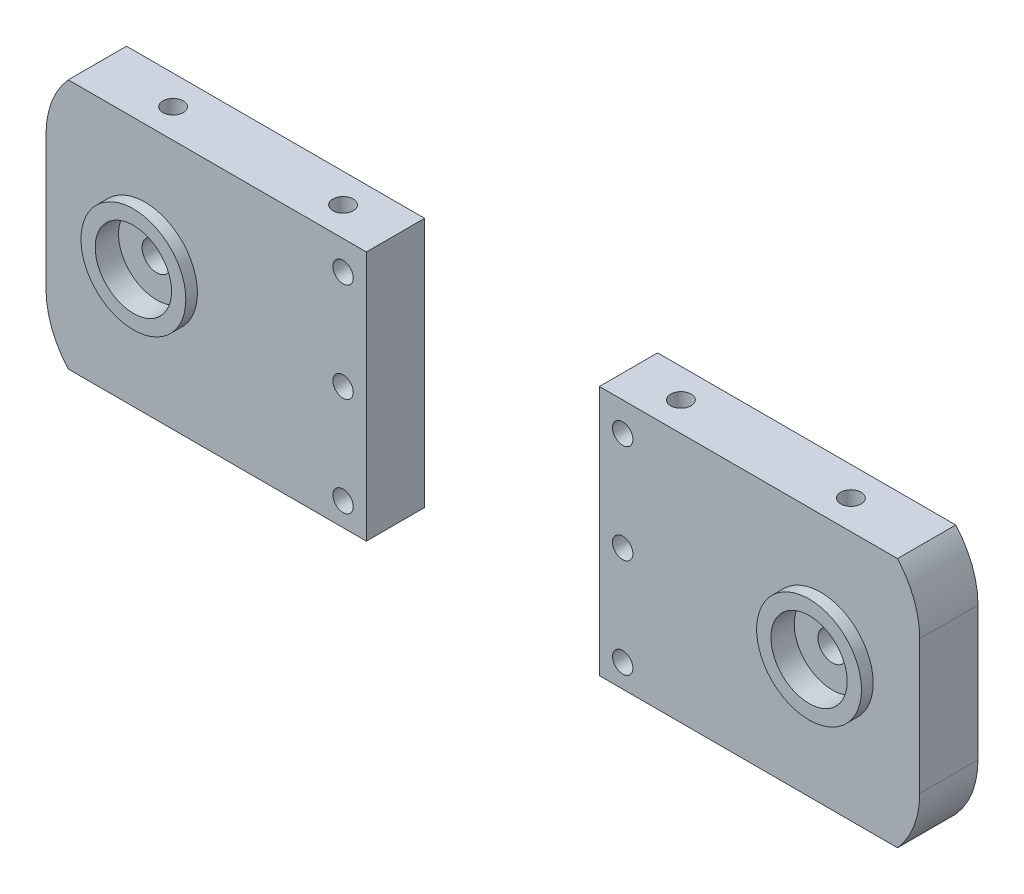
SolidWorks part; units mm, degrees
ref_plane "Ön Düzlem" through (0, 0, 0) normal (0, 0, 1) x (1, 0, 0)
ref_plane "Üst Düzlem" through (0, 0, 0) normal (0, 1, 0) x (1, 0, 0)
ref_plane "Sağ Düzlem" through (0, 0, 0) normal (1, 0, 0) x (0, 0, -1)
sketch "Çizim1" plane through (0, 0, 0) normal (0, 0, 1) x (1, 0, 0)
  line L1 (15, 0) -> (135, 0)
  line L2 (0, 15) -> (0, 38)
  line L3 (15, 53) -> (135, 53)
  line L4 (150, 15) -> (150, 38)
  line L5 (45, 53) -> (105, 53)
  line L6 (45, 53) -> (45, 0)
  line L7 (45, 0) -> (105, 0)
  line L8 (105, 53) -> (105, 0)
  line L9 (45, 53) -> (55, 53)
  line L10 (45, 53) -> (45, 0)
  line L11 (45, 0) -> (55, 0)
  line L12 (55, 53) -> (55, 0)
  line L13 (105, 53) -> (95, 53)
  line L14 (105, 53) -> (105, 1.2346)
  line L15 (105, 1.2346) -> (95, 1.2346)
  line L16 (95, 53) -> (95, 1.2346)
  line L17 (55, 48) -> (95, 48)
  line L18 (55, 48) -> (55, 5)
  line L19 (55, 5) -> (95, 5)
  line L20 (95, 48) -> (95, 5)
  arc A0 (150, 15) -> (135, 0) centre (135, 15) cw
  arc A1 (150, 38) -> (135, 53) centre (135, 38) ccw
  arc A2 (15, 0) -> (0, 15) centre (15, 15) cw
  arc A3 (15, 53) -> (0, 38) centre (15, 38) ccw
  circle A4 centre (17, 27.41) radius 12.5
  circle A5 centre (133, 27.41) radius 12.5
  circle A6 centre (51, 43) radius 1.75
  circle A7 centre (51, 26) radius 1.75
  circle A8 centre (51, 9) radius 1.75
  circle A9 centre (99, 26) radius 1.75
  circle A10 centre (99, 9) radius 1.75
  circle A11 centre (99, 43) radius 1.75
  point P11 (0, 0)
  dimension "D1" = 15
  dimension "D2" = 17
  dimension "D4" = 27.41
  dimension "D5" = 27.41
  dimension "D8" = 4
  dimension "D9" = 10
  dimension "D3" = 17
  dimension "D6" = 60
  dimension "D7" = 45
  dimension "D12" = 5
  dimension "D13" = 5
  dimension "D10" = 3
  dimension "D11" = 2
extrude "Yükseklik-Ekstrüzyon1" add sketch "Çizim1" along normal blind 10 contours L3 A3 L2 A2 L1 L6 A4 | L12 L3 L6 L1 A8 A7 A6 | L3 L16 L1 L8 A11 A10 A9 | L4 A1 L3 L8 L1 A0 A5 | L12 L17 L16 L5 | L19 L12 L7 L8 L15 L16
sketch "Çizim7" plane through (0, 0, 0) normal (0, 0, -1) x (-1, 0, 0)
  circle A0 centre (-133, 27.41) radius 12.5
  circle A1 centre (-133, 27.41) radius 2.5
extrude "Yükseklik-Ekstrüzyon8" add sketch "Çizim7" against normal blind 4 from offset 4 offset against normal yes
sketch "Çizim8" plane through (0, 0, 8) normal (0, 0, 1) x (1, 0, 0)
  circle A0 centre (133, 27.41) radius 2.5
  circle A1 centre (133, 27.41) radius 6.55
  circle A2 centre (133, 27.41) radius 9
extrude "Yükseklik-Ekstrüzyon9" add sketch "Çizim8" along normal blind 4 contours A2 A1
pattern_linear "LÇoğaltma1" count 2 spacing 116 along (-1, 0, 0) of "Yükseklik-Ekstrüzyon9", "Yükseklik-Ekstrüzyon8"
sketch "Çizim11" plane through (0, 0, 10) normal (0, 0, 1) x (1, 0, 0)
  line L0 (55, 48) -> (95, 48) construction
  line L1 (0, 5) -> (150, 5)
  line L2 (0, 5) -> (0, 48)
  line L3 (0, 48) -> (150, 48)
  line L4 (150, 5) -> (150, 48)
  line L5 (55, 5) -> (95, 5) construction
  line L7 (0, 48) -> (156.0546, 48)
  line L8 (0, 48) -> (0, 62.6003)
  line L9 (0, 62.6003) -> (156.0546, 62.6003)
  line L10 (156.0546, 48) -> (156.0546, 62.6003)
  line L11 (0, 5) -> (161.9978, 5)
  line L12 (0, 5) -> (0, -18.6878)
  line L13 (0, -18.6878) -> (161.9978, -18.6878)
  line L14 (161.9978, 5) -> (161.9978, -18.6878)
  line M2 (15, 0) -> (135, 0)
  arc M3 (135, 0) -> (150, 15) centre (135, 15) ccw
  arc M5 (150, 38) -> (135, 53) centre (135, 38) ccw
  line M6 (135, 53) -> (15, 53)
  arc M7 (15, 53) -> (0, 38) centre (15, 38) ccw
  arc M9 (0, 15) -> (15, 0) centre (15, 15) ccw
  line M11 (55, 48) -> (95, 48)
  line M15 (95, 5) -> (55, 5)
extrude "Kes-Ekstrüzyon3" cut sketch "Çizim11" against normal blind 10 contours L7 L10 L9 L8 L3 M7 M6 M5 | L3 M7 M11 M5 M6 | L1 M9 M2 M3 M15 | L14 L11 L1 L12 L13 M3 M2 M9
sketch "Çizim13" plane through (0, 0, 8) normal (0, 0, 1) x (1, 0, 0)
  circle A0 centre (133, 27.41) radius 12.5
  circle A1 centre (133, 27.41) radius 9
  circle A2 centre (17, 27.41) radius 12.5
  circle A3 centre (17, 27.41) radius 9
extrude "Yükseklik-Ekstrüzyon10" add sketch "Çizim13" along normal blind 2
sketch "Çizim12" plane through (0, 48, 0) normal (0, 1, 0) x (1, 0, 0)
  line L0 (55, -10) -> (55, 0) construction
  line L1 (3.8197, -10) -> (3.8197, 0) construction
  line L2 (95, -10) -> (95, 0) construction
  line L3 (146.1803, 0) -> (146.1803, -10) construction
  circle A0 centre (46, -5) radius 1.75
  circle A1 centre (16.8197, -5) radius 1.75
  circle A2 centre (104, -5) radius 1.75
  circle A3 centre (133.1803, -5) radius 1.75
  dimension "D1" = 9
  dimension "D3" = 9
  dimension "D2" = 13
  dimension "D4" = 13
extrude "Kes-Ekstrüzyon4" cut sketch "Çizim12" against normal blind 10
sketch "Çizim14" plane through (0, 5, 0) normal (0, -1, 0) x (1, 0, 0)
  line L0 (146.1803, 10) -> (146.1803, 0) construction
  line L1 (95, 10) -> (95, 0) construction
  line L2 (55, 10) -> (55, 0) construction
  line L3 (3.8197, 0) -> (3.8197, 10) construction
  circle A0 centre (16.8197, 5) radius 1.75
  circle A1 centre (46, 5) radius 1.75
  circle A2 centre (104, 5) radius 1.75
  circle A3 centre (133.1803, 5) radius 1.75
  dimension "D1" = 13
  dimension "D2" = 9
  dimension "D3" = 9
  dimension "D4" = 13
extrude "Kes-Ekstrüzyon5" cut sketch "Çizim14" against normal blind 10
